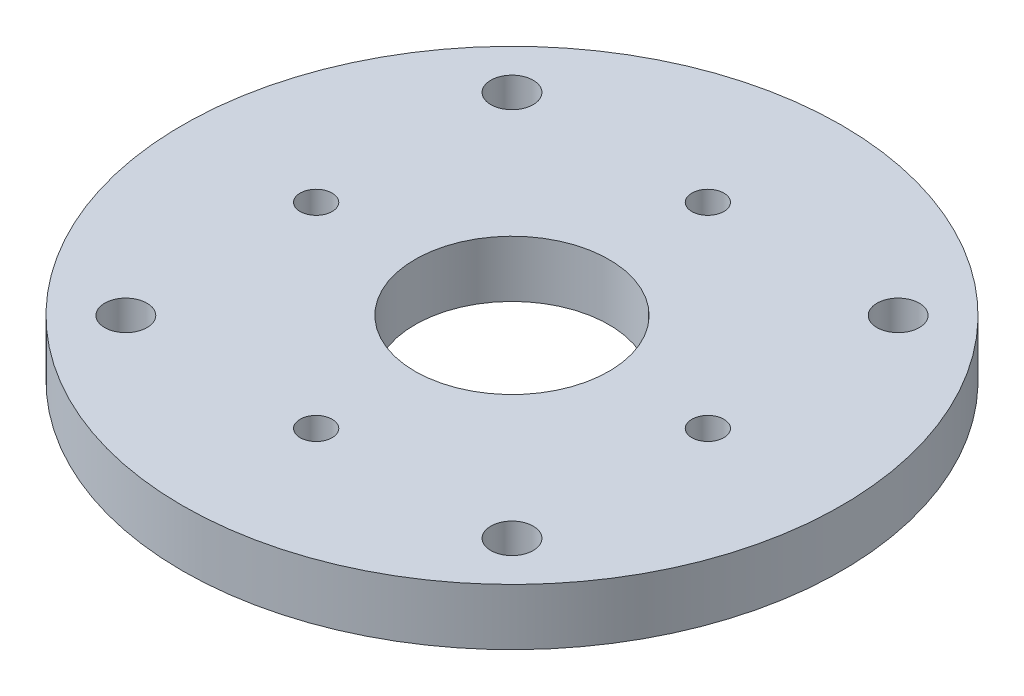
SolidWorks part; units mm, degrees
material "6061-T6 (SS)"
ref_plane "Front Plane" through (0, 0, 0) normal (0, 0, 1) x (1, 0, 0)
ref_plane "Top Plane" through (0, 0, 0) normal (0, 1, 0) x (1, 0, 0)
ref_plane "Right Plane" through (0, 0, 0) normal (1, 0, 0) x (0, 0, -1)
sketch "Sketch1" plane through (0, 0, 0) normal (0, 1, 0) x (1, 0, 0)
  circle A0 centre (0, 0) radius 35
  circle A1 centre (0, 0) radius 10.3
  dimension "D1" = 70
  dimension "D2" = 20.6
extrude "Boss-Extrude1" add sketch "Sketch1" along normal blind 6
sketch "Sketch3" plane through (0, 6, 0) normal (0, 1, 0) x (1, 0, 0)
  circle A0 centre (0, 0) radius 20.8 construction
  circle A1 centre (-20.8, 0) radius 1.7
  circle A2 centre (0, 20.8) radius 1.7
  circle A3 centre (0, 0) radius 20.8 construction
  circle A4 centre (20.8, 0) radius 1.7
  circle A5 centre (0, 0) radius 20.8 construction
  circle A6 centre (0, -20.8) radius 1.7
  circle A7 centre (0, 0) radius 20.8 construction
  point P16 (0, 0)
  dimension "D1" = 41.6
  dimension "D2" = 3.4
  dimension "D3" = 4
extrude "Cut-Extrude1" cut sketch "Sketch3" against normal through all
sketch "Sketch5" plane through (0, 6, 0) normal (0, 1, 0) x (1, 0, 0)
  line L0 (0, 29) -> (-29, 0) construction
  line L1 (0, 0) -> (-20.5061, -20.5061) construction
  line L2 (0, 0) -> (-14.5, 14.5) construction
  line L3 (-14.5, 14.5) -> (20.5061, -20.5061) construction
  line L4 (0, 0) -> (20.5061, 20.5061) construction
  line L5 (-14.5, 14.5) -> (-20.5061, 20.5061) construction
  circle A0 centre (0, 0) radius 29 construction
  circle A1 centre (-20.5061, 20.5061) radius 2.25
  circle A2 centre (-20.5061, -20.5061) radius 2.25
  circle A3 centre (0, 0) radius 29 construction
  circle A4 centre (20.5061, 20.5061) radius 2.25
  circle A5 centre (0, 0) radius 29 construction
  circle A6 centre (20.5061, -20.5061) radius 2.25
  circle A7 centre (0, 0) radius 29 construction
  point P23 (0, 0)
  dimension "D1" = 58
  dimension "D4" = 4.5
  dimension "D2" = 90
  dimension "D3" = 90
  dimension "D5" = 4
extrude "Cut-Extrude2" cut sketch "Sketch5" against normal through all
equation "\"D1@Boss-Extrude1\"=\"HUB_UpperStructuralRetainerThk\""
equation "\"D2@Sketch1\"=\"HUB_UpperRetainerCenterClearDia\""
equation "\"D1@Sketch1\"=\"HUB_UpperStructuralRetainerOD\""
equation "\"D1@Sketch3\"=\"HUB_RetainerBCDia\""
equation "\"D2@Sketch3\"=\"HUB_RetainerClearDia\""
equation "\"D1@Sketch5\"=\"HUB_DeckMountBCDia\""
equation "\"D4@Sketch5\"=\"HUB_DeckMountClearDia\""
equation "\"____ VERSION / MIRROR CONTROL ____\" = 0"
equation "\"SYS_VersionTag\" = 2.00"
equation "\"____ BEARING BLOCK ____\" = 0"
equation "\"BRG_BearingOD\" = 22mm"
equation "\"____ HUB SEATS + BRIDGE ____\" = 0"
equation "\"HUB_MainBodyOD\" = 48mm"
equation "\"____ HUB RETAINERS + DECK INTERFACE ____\" = 0"
equation "\"HUB_RetainerScrewSize\" = 3mm"
equation "\"HUB_RetainerScrewCount\" = 4"
equation "\"HUB_RetainerClearDia\" = 3.4mm"
equation "\"HUB_RetainerEdgeMin\" = 1.5mm"
equation "\"HUB_RetainerBoltR\" = (\"HUB_MainBodyOD\" / 2) - (\"HUB_RetainerClearDia\" / 2) - \"HUB_RetainerEdgeMin\""
equation "\"HUB_RetainerBCDia\" = 2*\"HUB_RetainerBoltR\""
equation "\"____ HUB RETAINER THREAD / BLIND-HOLE MACHINING INTENT ____\" = 0"
equation "\"HUB_RetainerThreadEngagementMin\" = 3.0mm"
equation "\"HUB_RetainerThreadEngagementTarget\" = 4.5mm"
equation "\"HUB_RetainerScrewIntoHubTarget\" = \"HUB_RetainerThreadEngagementTarget\""
equation "\"HUB_RetainerScrewIntoHubMin\" = \"HUB_RetainerThreadEngagementMin\""
equation "\"HUB_UpperStructuralRetainerThk\" = 6.0mm"
equation "\"HUB_UpperStructuralRetainerOD\" = 70mm"
equation "\"HUB_UpperRetainerCenterClearDia\" = 20.6mm"
equation "\"HUB_DeckMountCount\" = 4"
equation "\"HUB_DeckMountClearDia\" = 4.5mm"
equation "\"HUB_DeckMountBCDia\" = 58mm"
equation "\"____ HUB VARIABLE COMPATIBILITY ALIASES (KEEP v2.00 MAP STABLE) ____\" = 0"
equation "\"HUB_UpperRetainerThk\" = \"HUB_UpperStructuralRetainerThk\""
equation "\"HUB_UpperRetainerOD\" = \"HUB_UpperStructuralRetainerOD\""
equation "\"HUB_UpperRetainerCenterHoleDia\" = \"HUB_UpperRetainerCenterClearDia\""
equation "\"____ GENERATED EXPORTS ____\" = 0"
equation "\"USR_MinScrewReach\" = \"HUB_UpperRetainerThk\" + \"HUB_RetainerScrewIntoHubMin\""
equation "\"USR_RecommendedScrewReach\" = \"HUB_UpperRetainerThk\" + \"HUB_RetainerScrewIntoHubTarget\""
